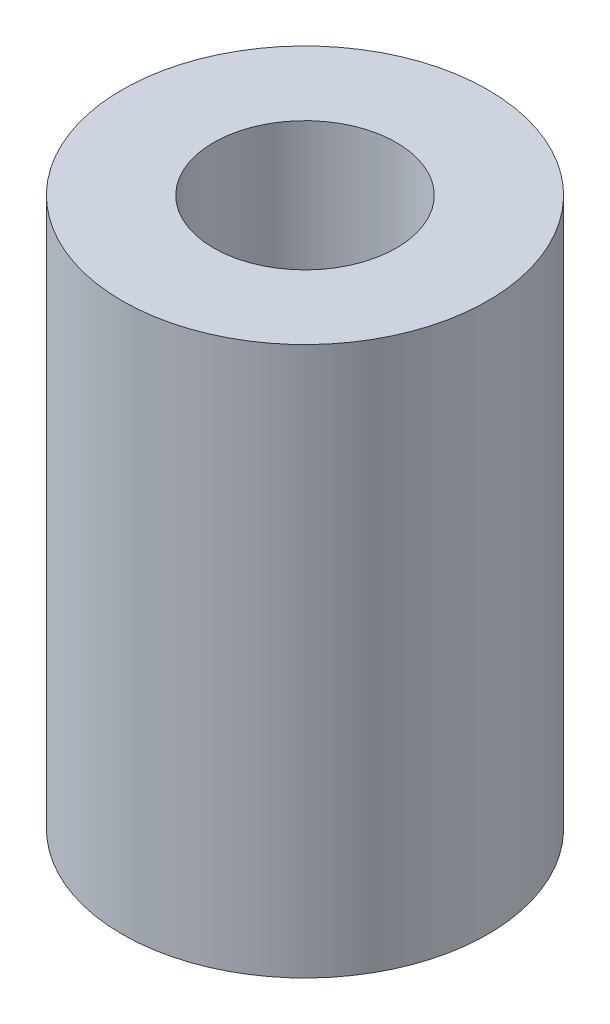
SolidWorks part; units mm, degrees
material "Vero PureWhite"
ref_plane "前视基准面" through (0, 0, 0) normal (0, 0, 1) x (1, 0, 0)
ref_plane "上视基准面" through (0, 0, 0) normal (0, 1, 0) x (1, 0, 0)
ref_plane "右视基准面" through (0, 0, 0) normal (1, 0, 0) x (0, 0, -1)
sketch "草图1" plane through (0, 0, 0) normal (0, 1, 0) x (1, 0, 0)
  circle A0 centre (0, 0) radius 5
  circle A1 centre (0, 0) radius 2.5
  dimension "D1" = 5
  dimension "D2" = 10
extrude "凸台-拉伸1" add sketch "草图1" along normal blind 15
scale "缩放比例1" scale about origin uniform scaling yes scale factor 0.6
